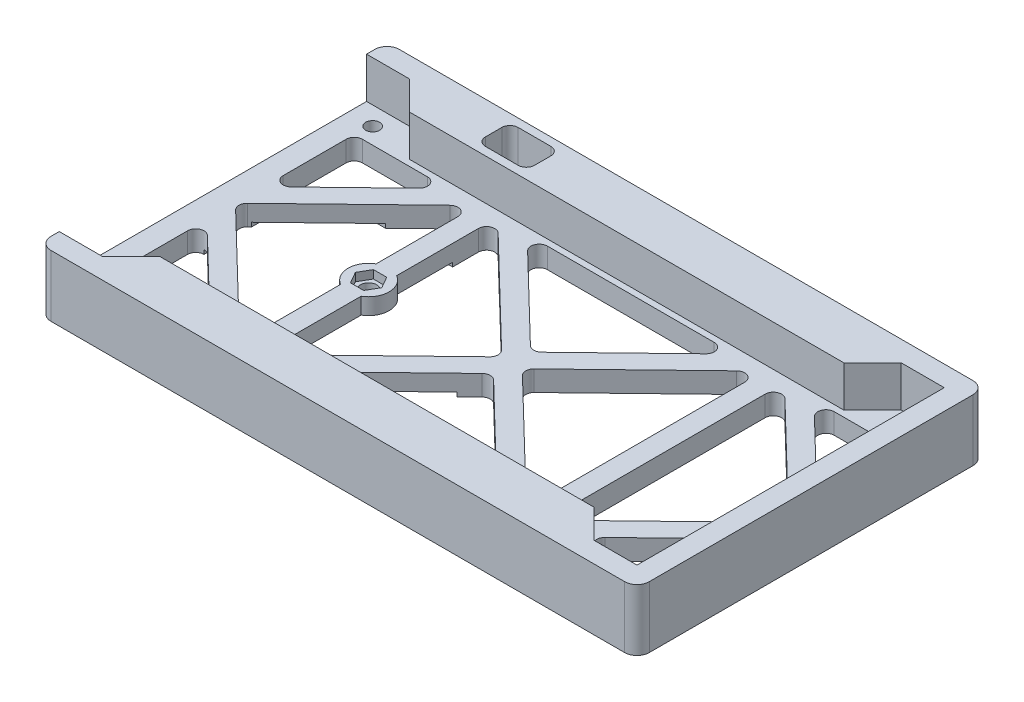
SolidWorks part; units mm, degrees
material "ABS PC"
ref_plane "Front Plane" through (0, 0, 0) normal (0, 0, 1) x (1, 0, 0)
ref_plane "Top Plane" through (0, 0, 0) normal (0, 1, 0) x (1, 0, 0)
ref_plane "Right Plane" through (0, 0, 0) normal (1, 0, 0) x (0, 0, -1)
sketch "Sketch1" plane through (0, 0, 0) normal (0, 1, 0) x (1, 0, 0)
  line L1 (73, -42.5) -> (-73, -42.5)
  line L2 (73, -42.5) -> (73, 42.5)
  line L3 (73, 42.5) -> (-73, 42.5)
  line L4 (-73, -42.5) -> (-73, 42.5)
  line L5 (73, -42.5) -> (-73, 42.5) construction
  line L6 (73, 42.5) -> (-73, -42.5) construction
  point P0 (0, 0)
  dimension "D1" = 146
  dimension "D2" = 85
extrude "Boss-Extrude1" add sketch "Sketch1" along normal blind 15
shell "Shell1" thickness 5
sketch "Sketch2" plane through (0, 15, 0) normal (0, 1, 0) x (1, 0, 0)
  line L0 (-73, 42.5) -> (-73, -42.5) construction
  line L1 (-68, 37.5) -> (-73, 37.5)
  line L2 (-68, 37.5) -> (-68, -37.5)
  line L3 (-68, -37.5) -> (-73, -37.5)
  line L4 (-73, 37.5) -> (-73, -37.5)
extrude "Cut-Extrude1" cut sketch "Sketch2" against normal up to surface (10 mm away) up to face at (0, 5, 0)
sketch "Sketch3" plane through (0, 5, 0) normal (0, 1, 0) x (1, 0, 0)
  line L0 (-29.7548, 0) -> (34.5948, 0) construction
  line L1 (-2.5, 30.5) -> (-2.5, 37.5) construction
  line L2 (68, 37.5) -> (-73, 37.5) construction
  line L3 (-55.5, 30.5) -> (50.5, 30.5)
  line L4 (50.5, 30.5) -> (57.5, 37.5)
  line L5 (57.5, 37.5) -> (-62.5, 37.5)
  line L6 (-55.5, 30.5) -> (-62.5, 37.5)
  line L7 (-55.5, -30.5) -> (-62.5, -37.5)
  line L8 (57.5, -37.5) -> (-62.5, -37.5)
  line L9 (50.5, -30.5) -> (57.5, -37.5)
  line L10 (-55.5, -30.5) -> (50.5, -30.5)
  dimension "D1" = 7
  dimension "D2" = 120
  dimension "D3" = 45
extrude "Boss-Extrude2" add sketch "Sketch3" along normal up to surface (10 mm away) up to face at (-1.25, 15, 0)
hole_wizard "CSK for M3 Flat Head Machine Screw1" positions "Sketch5" profile "Sketch6" countersink size "M3" standard "ANSI Metric"
sketch "Sketch5" plane through (0, 0, 0) normal (0, -1, 0) x (-1, 0, 0)
  line L1 (67, 33) -> (-63, 33)
  line L2 (67, 33) -> (67, -33)
  line L3 (67, -33) -> (-63, -33)
  line L4 (-63, 33) -> (-63, -33)
  line L5 (67, 33) -> (-63, -33) construction
  line L6 (67, -33) -> (-63, 33) construction
  line L7 (0, 0) -> (2, 0) construction
  point P2 (-63, -33)
  point P5 (67, 33)
  point P6 (67, -33)
  point P7 (-63, 33)
  dimension "D1" = 130
  dimension "D2" = 66
  dimension "D3" = 2
sketch "Sketch6" plane through (63, 0, 33) normal (1, 0, 0) x (0, 0, -1)
  line L0 (0, 0) -> (0, 11.0215)
  line L1 (0, 11.0215) -> (1.7, 10)
  line L2 (1.7, 10) -> (1.7, 1.45)
  line L3 (1.7, 1.45) -> (3.15, 0)
  line L5 (3.15, 0) -> (0, 0)
  line L6 (-1.7, 1.45) -> (-3.15, 0) construction
  line L10 (0, 11.0215) -> (-1.7, 10) construction
  line L11 (0, -6.35) -> (0, 107.95) construction
  dimension "Hole Dia." = 3.4
  dimension "Hole Depth" = 10
  dimension "Near C'Sink Dia." = 6.3
  dimension "Near C'Sink Angle" = 90
  dimension "Drill Angle" = 118
fillet "Fillet1" radius 3 4 edges at (-73, 7.5, 42.5) (73, 7.5, 42.5) (-73, 7.5, -42.5) (73, 7.5, -42.5)
sketch "Sketch7" plane through (0, 0, 0) normal (0, -1, 0) x (1, 0, 0)
  circle A0 centre (-67, 33) radius 3.5
  circle A1 centre (-67, -33) radius 3.5
  circle A2 centre (63, -33) radius 3.5
  circle A3 centre (63, 33) radius 3.5
  dimension "D1" = 7
extrude "Cut-Extrude2" [suppressed] cut sketch "Sketch7" against normal blind 3
sketch "Sketch8" plane through (0, 0, 0) normal (0, -1, 0) x (1, 0, 0)
  line L0 (67.5, 0) -> (37.5, 0) construction
  line L1 (67.5, 0) -> (37.5, 29)
  line L2 (37.5, 29) -> (37.5, -29)
  line L3 (67.5, 0) -> (37.5, -29)
  line L4 (0, 4.5375) -> (25.306, 29)
  line L5 (35, 14.6198) -> (35, -42.8998) construction
  line L6 (2.5, 0) -> (32.5, -29)
  line L7 (32.5, 29) -> (32.5, -29)
  line L8 (2.5, 0) -> (32.5, 29)
  line L9 (0, 42.5) -> (0, -42.5) construction
  line L10 (-70, 42.5) -> (70, 42.5) construction
  line L11 (70, -42.5) -> (-70, -42.5) construction
  line L12 (-2.5, 0) -> (-32.5, 29)
  line L13 (-32.5, 29) -> (-32.5, -29)
  line L14 (-2.5, 0) -> (-32.5, -29)
  line L15 (-67.5, 0) -> (-37.5, -29)
  line L16 (-37.5, 29) -> (-37.5, -29)
  line L17 (-67.5, 0) -> (-37.5, 29)
  line L19 (0, 4.5375) -> (-25.306, 29)
  line L20 (-25.306, 29) -> (25.306, 29)
  line L21 (-44.694, 29) -> (-67.5, 29)
  line L22 (-67.5, 29) -> (-67.5, 6.9542)
  line L23 (-67.5, 6.9542) -> (-44.694, 29)
  line L24 (67.5, 6.9542) -> (44.694, 29)
  line L25 (67.5, 29) -> (67.5, 6.9542)
  line L26 (44.694, 29) -> (67.5, 29)
  line L27 (44.694, -29) -> (67.5, -29)
  line L28 (67.5, -29) -> (67.5, -6.9542)
  line L29 (67.5, -6.9542) -> (44.694, -29)
  line L30 (-67.5, -6.9542) -> (-44.694, -29)
  line L31 (-67.5, -29) -> (-67.5, -6.9542)
  line L32 (-44.694, -29) -> (-67.5, -29)
  line L33 (-25.306, -29) -> (25.306, -29)
  line L34 (0, -4.5375) -> (-25.306, -29)
  line L35 (0, -4.5375) -> (25.306, -29)
  point P31 (0, 29)
  dimension "D1" = 58
  dimension "D2" = 5
  dimension "D3" = 30
  dimension "D4" = 5
  dimension "D5" = 5
  dimension "D6" = 5
extrude "Cut-Extrude3" cut sketch "Sketch8" against normal blind 10
fillet "Fillet2" radius 2 30 edges at (-37.5, 2.5, -29) (-67.5, 2.5, 0) (-37.5, 2.5, 29) (-32.5, 2.5, -29) (-2.5, 2.5, 0) (-32.5, 2.5, 29) (32.5, 2.5, -29) (2.5, 2.5, 0) (32.5, 2.5, 29) (37.5, 2.5, -29) (37.5, 2.5, 29) (67.5, 2.5, 0) (67.5, 2.5, 6.9542) (44.694, 2.5, 29) (67.5, 2.5, 29) (67.5, 2.5, -6.9542) (67.5, 2.5, -29) (44.694, 2.5, -29) (-67.5, 2.5, -6.9542) (-44.694, 2.5, -29) (-67.5, 2.5, -29) (-67.5, 2.5, 6.9542) (-44.694, 2.5, 29) (-67.5, 2.5, 29) (0, 2.5, -4.5375) (25.306, 2.5, -29) (-25.306, 2.5, -29) (25.306, 2.5, 29) (0, 2.5, 4.5375) (-25.306, 2.5, 29)
sketch "Sketch9" plane through (0, 5, 0) normal (0, 1, 0) x (1, 0, 0)
  circle A0 centre (0, 0) radius 6
  dimension "D1" = 12
extrude "Boss-Extrude3" [suppressed] add sketch "Sketch9" against normal through all
hole_wizard "Ø4.0 (4) Diameter Hole1" [suppressed] positions "Sketch10" profile "Sketch11" hole size "Ø4.0" standard "ANSI Metric"
sketch "Sketch10" plane through (0, 5, 0) normal (0, 1, 0) x (1, 0, 0)
  point P0 (0, 0)
sketch "Sketch11" plane through (0, 5, 0) normal (1, 0, 0) x (0, 0, 1)
  line L0 (0, 0) -> (0, 11.2017)
  line L1 (0, 11.2017) -> (2, 10)
  line L2 (2, 10) -> (2, 0)
  line L5 (2, 0) -> (0, 0)
  line L10 (0, 11.2017) -> (-2, 10) construction
  line L11 (0, -6.35) -> (0, 107.95) construction
  dimension "Hole Dia." = 4
  dimension "Hole Depth" = 10
  dimension "Drill Angle" = 118
sketch "Sketch12" plane through (0, 5, 0) normal (0, 1, 0) x (1, 0, 0)
  line L1 (3.2332, 0) -> (1.6166, 2.8)
  line L2 (1.6166, 2.8) -> (-1.6166, 2.8)
  line L3 (-1.6166, 2.8) -> (-3.2332, 0)
  line L4 (-3.2332, 0) -> (-1.6166, -2.8)
  line L5 (-1.6166, -2.8) -> (1.6166, -2.8)
  line L6 (1.6166, -2.8) -> (3.2332, 0)
  circle A0 centre (0, 0) radius 2.8 construction
  dimension "D1" = 5.6
extrude "Cut-Extrude4" [suppressed] cut sketch "Sketch12" against normal blind 3
sketch "Sketch13" plane through (0, 0, 0) normal (0, -1, 0) x (1, 0, 0)
  line L0 (70, -42.5) -> (-70, -42.5) construction
  line L1 (-29, -32.5) -> (-41, -32.5)
  line L2 (-29, -32.5) -> (-29, -40.5)
  line L3 (-29, -40.5) -> (-41, -40.5)
  line L4 (-41, -32.5) -> (-41, -40.5)
  line L5 (-29, -32.5) -> (-41, -40.5) construction
  line L6 (-29, -40.5) -> (-41, -32.5) construction
  line L7 (-35, -36.5) -> (-35, -9.4194) construction
  line L8 (-32.5, -9.4194) -> (-37.5, -9.4194) construction
  line L9 (-37.5, -24.285) -> (-37.5, 24.285) construction
  line L10 (-32.5, 24.285) -> (-32.5, -24.285) construction
  point P0 (-35, -36.5)
  point P15 (-35, -9.4194)
  dimension "D1" = 12
  dimension "D2" = 8
  dimension "D3" = 2
extrude "Cut-Extrude5" cut sketch "Sketch13" against normal through all
fillet "Fillet3" radius 2 4 edges at (-41, 7.5, -32.5) (-29, 7.5, -32.5) (-29, 7.5, -40.5) (-41, 7.5, -40.5)
sketch "Sketch14" plane through (0, 5, 0) normal (0, 1, 0) x (1, 0, 0)
  line L0 (-35, 0) -> (0, 0) construction
  line L1 (-32.5, 0) -> (-37.5, 0) construction
  line L2 (-37.5, -24.285) -> (-37.5, 24.285) construction
  line L3 (-32.5, 24.285) -> (-32.5, -24.285) construction
  circle A0 centre (-35, 0) radius 5
  point P9 (-35, 0)
  dimension "D1" = 10
extrude "Boss-Extrude4" add sketch "Sketch14" against normal through all
hole_wizard "Ø4.0 (4) Diameter Hole2" positions "Sketch15" profile "Sketch16" hole size "Ø4.0" standard "ANSI Metric" end condition through all
sketch "Sketch15" plane through (0, 5, 0) normal (0, 1, 0) x (1, 0, 0)
  point P0 (-35, 0)
sketch "Sketch16" plane through (-35, 5, 0) normal (1, 0, 0) x (0, 0, 1)
  line L0 (0, 0) -> (0, 5)
  line L1 (0, 5) -> (2, 5)
  line L2 (2, 5) -> (2, 0)
  line L5 (2, 0) -> (0, 0)
  line L11 (0, -6.35) -> (0, 107.95) construction
  dimension "Thru Hole Dia." = 4
  dimension "Thru Hole Depth" = 5
sketch "Sketch17" plane through (0, 5, 0) normal (0, 1, 0) x (1, 0, 0)
  line L1 (-31.7668, 0) -> (-33.3834, 2.8)
  line L2 (-33.3834, 2.8) -> (-36.6166, 2.8)
  line L3 (-36.6166, 2.8) -> (-38.2332, 0)
  line L4 (-38.2332, 0) -> (-36.6166, -2.8)
  line L5 (-36.6166, -2.8) -> (-33.3834, -2.8)
  line L6 (-33.3834, -2.8) -> (-31.7668, 0)
  circle A0 centre (-35, 0) radius 2.8 construction
  dimension "D1" = 5.6
extrude "Cut-Extrude6" cut sketch "Sketch17" against normal blind 2
sketch "Sketch19" plane through (0, 0, 0) normal (0, -1, 0) x (1, 0, 0)
  line L1 (-65.5, -18) -> (-4.5, -18)
  line L2 (-65.5, -18) -> (-65.5, 18)
  line L3 (-65.5, 18) -> (-4.5, 18)
  line L4 (-4.5, -18) -> (-4.5, 18)
  line L5 (-65.5, -18) -> (-4.5, 18) construction
  line L6 (-65.5, 18) -> (-4.5, -18) construction
  point P0 (-35, 0)
  dimension "D1" = 61
  dimension "D2" = 36
extrude "Cut-Extrude7" cut sketch "Sketch19" against normal blind 1
